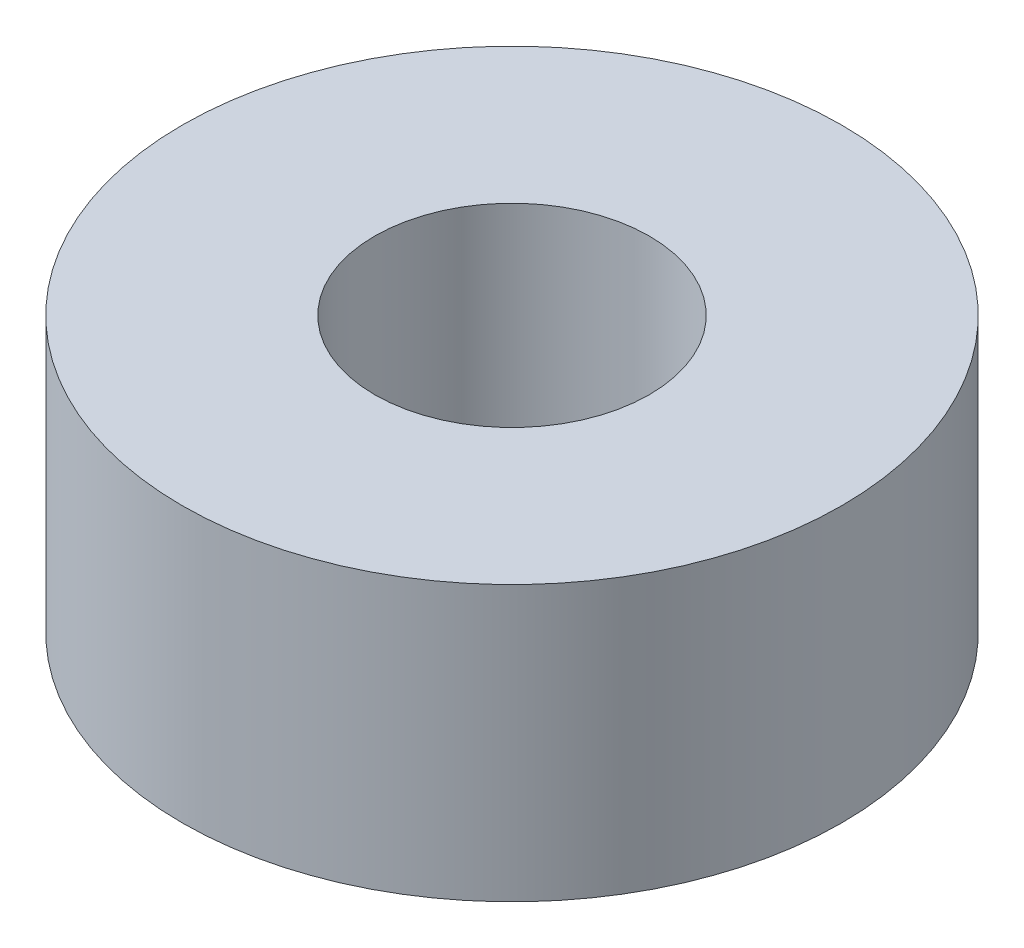
SolidWorks part; units mm, degrees
ref_plane "Front Plane" through (0, 0, 0) normal (0, 0, 1) x (1, 0, 0)
ref_plane "Top Plane" through (0, 0, 0) normal (0, 1, 0) x (1, 0, 0)
ref_plane "Right Plane" through (0, 0, 0) normal (1, 0, 0) x (0, 0, -1)
sketch "Sketch1" plane through (0, 0, 0) normal (0, 1, 0) x (1, 0, 0)
  circle A0 centre (0, 0) radius 6
  circle A1 centre (0, 0) radius 2.5
  dimension "D1" = 12
  dimension "D2" = 5
extrude "Boss-Extrude1" add sketch "Sketch1" along normal blind 5
